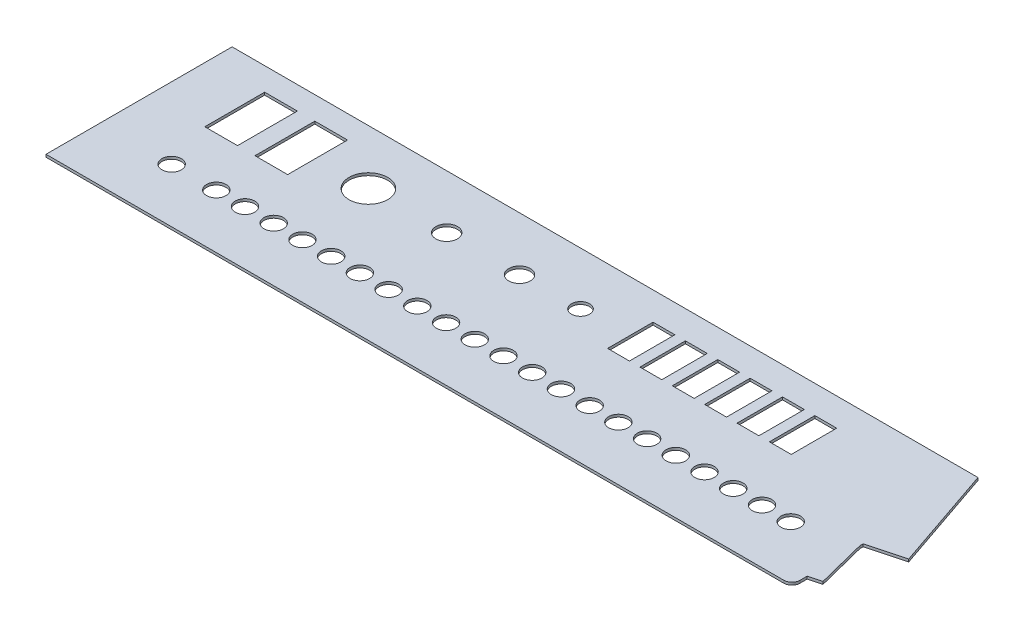
SolidWorks part; units mm, degrees
ref_plane "Front Plane" through (0, 0, 0) normal (0, 0, 1) x (1, 0, 0)
ref_plane "Top Plane" through (0, 0, 0) normal (0, 1, 0) x (1, 0, 0)
ref_plane "Right Plane" through (0, 0, 0) normal (1, 0, 0) x (0, 0, -1)
sketch "Boceto" plane through (0, 0, 0) normal (0, 1, 0) x (1, 0, 0)
  line L0 (-59.1, 30.6902) -> (-173.0029, 30.6902) construction
  line L5 (-59.1, -51.6098) -> (395.9, -51.6098) construction
  line L6 (-59.1, -51.6098) -> (-59.1, 63.3902) construction
  line L7 (-59.1, 63.3902) -> (395.9, 63.3902) construction
  line L8 (395.9, -51.6098) -> (395.9, 63.3902) construction
  line L9 (-28.6, 48.9902) -> (-8.6, 48.9902) construction
  line L10 (-28.6, 48.9902) -> (-28.6, 12.3902) construction
  line L11 (-28.6, 12.3902) -> (-8.6, 12.3902) construction
  line L12 (-8.6, 48.9902) -> (-8.6, 12.3902) construction
  line L13 (-28.6, 48.9902) -> (-8.6, 12.3902) construction
  line L14 (-28.6, 12.3902) -> (-8.6, 48.9902) construction
  line L15 (-59.1, -18.1098) -> (395.9, -18.1098) construction
  line L16 (2.4, 12.3902) -> (22.4, 12.3902) construction
  line L17 (2.4, 12.3902) -> (2.4, 48.9902) construction
  line L18 (2.4, 48.9902) -> (22.4, 48.9902) construction
  line L19 (22.4, 12.3902) -> (22.4, 48.9902) construction
  line L20 (2.4, 12.3902) -> (22.4, 48.9902) construction
  line L21 (2.4, 48.9902) -> (22.4, 12.3902) construction
  line L22 (174.9, 49.7902) -> (194.9, 49.7902) construction
  line L23 (174.9, 49.7902) -> (174.9, 11.7902) construction
  line L24 (174.9, 11.7902) -> (194.9, 11.7902) construction
  line L25 (194.9, 49.7902) -> (194.9, 11.7902) construction
  line L26 (174.9, 49.7902) -> (194.9, 11.7902) construction
  line L27 (174.9, 11.7902) -> (194.9, 49.7902) construction
  line L34 (211.4, 17.5561) -> (331, 17.5561) construction
  line L35 (211.4, 17.5561) -> (211.4, 46.5902) construction
  line L36 (211.4, 46.5902) -> (331, 46.5902) construction
  line L37 (331, 17.5561) -> (331, 46.5902) construction
  line L38 (211.4, 17.5561) -> (331, 46.5902) construction
  line L39 (211.4, 46.5902) -> (331, 17.5561) construction
  circle A0 centre (54.9, 29.6902) radius 11.1 construction
  circle A1 centre (102.75, 30.2402) radius 4.85 construction
  circle A2 centre (147.75, 30.2402) radius 4.85 construction
  circle A3 centre (-18.9, -18.1098) radius 6 construction
  circle A4 centre (8.7, -18.1098) radius 6 construction
  circle A5 centre (26.45, -18.1098) radius 6 construction
  circle A6 centre (44.2, -18.1098) radius 6 construction
  circle A7 centre (61.95, -18.1098) radius 6 construction
  circle A8 centre (79.7, -18.1098) radius 6 construction
  circle A9 centre (97.45, -18.1098) radius 6 construction
  circle A10 centre (115.2, -18.1098) radius 6 construction
  circle A11 centre (132.95, -18.1098) radius 6 construction
  circle A12 centre (150.7, -18.1098) radius 6 construction
  circle A13 centre (168.45, -18.1098) radius 6 construction
  circle A14 centre (186.2, -18.1098) radius 6 construction
  circle A15 centre (203.95, -18.1098) radius 6 construction
  circle A16 centre (221.7, -18.1098) radius 6 construction
  circle A17 centre (239.45, -18.1098) radius 6 construction
  circle A18 centre (257.2, -18.1098) radius 6 construction
  circle A19 centre (274.95, -18.1098) radius 6 construction
  circle A20 centre (292.7, -18.1098) radius 6 construction
  circle A21 centre (310.45, -18.1098) radius 6 construction
  circle A22 centre (328.2, -18.1098) radius 6 construction
  circle A23 centre (345.95, -18.1098) radius 6 construction
  circle A24 centre (363.7, -18.1098) radius 6 construction
  point P0 (0, 0)
  point P6 (-18.6, 30.6902)
  point P13 (12.4, 30.6902)
  point P24 (184.9, 30.7902)
  point P34 (271.2, 32.0731)
  dimension "D10" = 22.2
  dimension "D11" = 33.7
  dimension "D14" = 9.7
  dimension "D17" = 9.7
  dimension "D23" = 12
  dimension "D29" = 81.5
  dimension "D30" = 12
  dimension "D1" = 455
  dimension "D2" = 115
  dimension "D3" = 14.4
  dimension "D4" = 30.5
  dimension "D5" = 20
  dimension "D6" = 36.6
  dimension "D7" = 11
  dimension "D8" = 20
  dimension "D9" = 36.6
  dimension "D12" = 114
  dimension "D13" = 161.85
  dimension "D15" = 33.15
  dimension "D16" = 33.15
  dimension "D18" = 206.85
  dimension "D19" = 20
  dimension "D20" = 38
  dimension "D21" = 13.6
  dimension "D22" = 234
  dimension "D24" = 270.5
  dimension "D25" = 119.6
  dimension "D26" = 16.8
  dimension "D27" = 29.0341
  dimension "D28" = 40.2
  dimension "D31" = 27.6
  dimension "D32" = 21
sketch "Sketch4" plane through (0, 0, 0) normal (0, 1, 0) x (1, 0, 0)
  line L0 (-28.6, 48.9902) -> (-8.6, 12.3902) construction
  line L5 (-28.7093, 12.1902) -> (-8.4907, 12.1902)
  line L6 (-28.7093, 12.1902) -> (-28.7093, 49.1902)
  line L7 (-28.7093, 49.1902) -> (-8.4907, 49.1902)
  line L8 (-8.4907, 12.1902) -> (-8.4907, 49.1902)
  line L9 (-28.7093, 12.1902) -> (-8.4907, 49.1902) construction
  line L10 (-28.7093, 49.1902) -> (-8.4907, 12.1902) construction
  line L11 (-28.6, 12.3902) -> (-8.6, 48.9902) construction
  line L12 (2.4, 12.3902) -> (22.4, 48.9902) construction
  line L17 (2.2907, 12.1902) -> (2.2907, 49.1902)
  line L18 (2.2907, 12.1902) -> (22.5093, 12.1902)
  line L19 (22.5093, 12.1902) -> (22.5093, 49.1902)
  line L20 (2.2907, 49.1902) -> (22.5093, 49.1902)
  line L21 (102.75, 30.2402) -> (199.8359, 30.2402) construction
  line L22 (211.4, 32.0731) -> (331, 32.0731) construction
  line L23 (211.4, 17.5561) -> (211.4, 46.5902) construction
  line L24 (331, 17.5561) -> (331, 46.5902) construction
  line L25 (247.9, 46.1231) -> (247.9, 18.0231)
  line L26 (227.9, 46.1231) -> (214.4, 46.1231)
  line L27 (227.9, 46.1231) -> (227.9, 18.0231)
  line L28 (227.9, 18.0231) -> (214.4, 18.0231)
  line L29 (214.4, 46.1231) -> (214.4, 18.0231)
  line L30 (227.9, 46.1231) -> (214.4, 18.0231) construction
  line L31 (227.9, 18.0231) -> (214.4, 46.1231) construction
  line L32 (247.9, 46.1231) -> (234.4, 46.1231)
  line L33 (234.4, 46.1231) -> (234.4, 18.0231)
  line L34 (247.9, 18.0231) -> (234.4, 18.0231)
  line L35 (267.9, 46.1231) -> (267.9, 18.0231)
  line L36 (267.9, 46.1231) -> (254.4, 46.1231)
  line L37 (254.4, 46.1231) -> (254.4, 18.0231)
  line L38 (267.9, 18.0231) -> (254.4, 18.0231)
  line L39 (287.9, 46.1231) -> (287.9, 18.0231)
  line L40 (287.9, 46.1231) -> (274.4, 46.1231)
  line L41 (274.4, 46.1231) -> (274.4, 18.0231)
  line L42 (287.9, 18.0231) -> (274.4, 18.0231)
  line L43 (307.9, 46.1231) -> (307.9, 18.0231)
  line L44 (307.9, 46.1231) -> (294.4, 46.1231)
  line L45 (294.4, 46.1231) -> (294.4, 18.0231)
  line L46 (307.9, 18.0231) -> (294.4, 18.0231)
  line L47 (327.9, 46.1231) -> (327.9, 18.0231)
  line L48 (327.9, 46.1231) -> (314.4, 46.1231)
  line L49 (314.4, 46.1231) -> (314.4, 18.0231)
  line L50 (327.9, 18.0231) -> (314.4, 18.0231)
  line L55 (-63.0474, 63.3902) -> (-63.0474, -51.6098)
  line L59 (397.9526, -46.6098) -> (397.9526, -42.1875)
  line L60 (-63.0474, 63.3902) -> (397.9526, 63.3902)
  line L62 (-63.0474, -51.6098) -> (392.9526, -51.6098)
  line L63 (397.9526, 63.3902) -> (420.1689, -1.657)
  line L64 (420.1689, -1.657) -> (397.9526, -7.6098)
  line L65 (397.9526, -9.6098) -> (405.68, -40.1169)
  line L66 (405.68, -40.1169) -> (397.9526, -42.1875)
  line L67 (397.9526, -9.6098) -> (397.9526, -7.6098)
  circle A0 centre (54.9, 29.6902) radius 11.95
  circle A1 centre (102.75, 30.2402) radius 6.65
  circle A4 centre (147.75, 30.2402) radius 6.65
  circle A6 centre (184.9, 30.7902) radius 5.6
  circle A7 centre (-18.9, -18.1098) radius 6
  circle A8 centre (8.7, -18.1098) radius 6
  circle A9 centre (26.45, -18.1098) radius 6
  circle A10 centre (44.2, -18.1098) radius 6
  circle A11 centre (61.95, -18.1098) radius 6
  circle A12 centre (79.7, -18.1098) radius 6
  circle A13 centre (97.45, -18.1098) radius 6
  circle A14 centre (115.2, -18.1098) radius 6
  circle A15 centre (132.95, -18.1098) radius 6
  circle A16 centre (150.7, -18.1098) radius 6
  circle A17 centre (168.45, -18.1098) radius 6
  circle A18 centre (186.2, -18.1098) radius 6
  circle A19 centre (203.95, -18.1098) radius 6
  circle A20 centre (221.7, -18.1098) radius 6
  circle A21 centre (239.45, -18.1098) radius 6
  circle A22 centre (257.2, -18.1098) radius 6
  circle A23 centre (274.95, -18.1098) radius 6
  circle A24 centre (292.7, -18.1098) radius 6
  circle A25 centre (310.45, -18.1098) radius 6
  circle A26 centre (328.2, -18.1098) radius 6
  circle A27 centre (345.95, -18.1098) radius 6
  circle A28 centre (363.7, -18.1098) radius 6
  arc A30 (392.9526, -51.6098) -> (397.9526, -46.6098) centre (392.9526, -46.6098) ccw
  point P6 (-18.6, 30.6902)
  point P15 (12.4, 30.6902)
  point P40 (221.15, 32.0731)
  dimension "D3" = 23.9
  dimension "D4" = 13.3
  dimension "D5" = 2
  dimension "D6" = 11.2
  dimension "D11" = 12
  dimension "D13" = 115
  dimension "D16" = 71
  dimension "D14" = 5
  dimension "D1" = 37
  dimension "D2" = 2
  dimension "D7" = 13.5
  dimension "D8" = 28.1
  dimension "D9" = 3
  dimension "D15" = 461
  dimension "D17" = 75
  dimension "D18" = 23
  dimension "D19" = 75
  dimension "D20" = 2
  dimension "D21" = 8
  dimension "D10" = 6
  dimension "D12" = 21
extrude "Boss-Extrude3" add sketch "Sketch4" along normal blind 1.6
